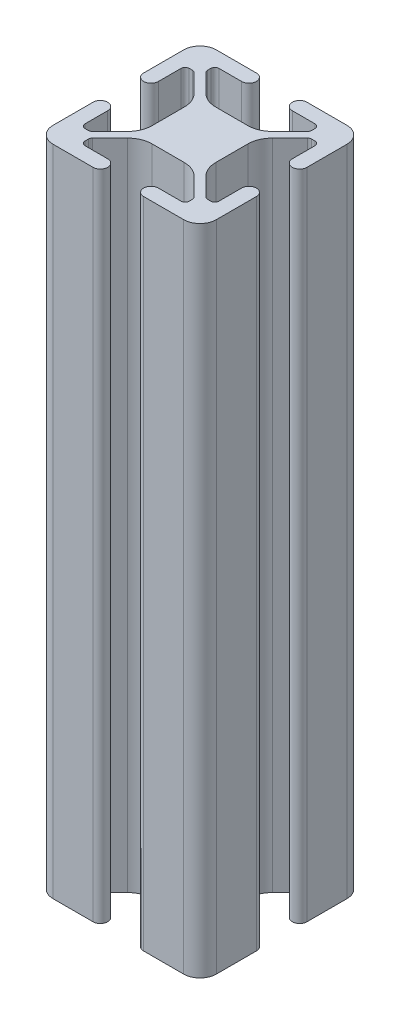
SolidWorks part; units mm, degrees
ref_plane "前视基准面" through (0, 0, 0) normal (0, 0, 1) x (1, 0, 0)
ref_plane "上视基准面" through (0, 0, 0) normal (0, 1, 0) x (1, 0, 0)
ref_plane "右视基准面" through (0, 0, 0) normal (1, 0, 0) x (0, 0, -1)
sketch "草图1" plane through (0, 0, 0) normal (0, 1, 0) x (1, 0, 0)
  line L0 (-1.0428, -10.0859) -> (3.8572, -10.0859)
  line L1 (1.0762, -11.8859) -> (3.8572, -11.8859)
  line L2 (2.8854, -15.3072) -> (0.7226, -13.1443)
  line L3 (2.1786, -16.0141) -> (0.0157, -13.8512)
  line L4 (-3.0428, -12.0859) -> (-3.0428, -16.9859)
  line L5 (-1.2428, -14.2048) -> (-1.2428, -16.9859)
  line L6 (-0.7428, -13.7048) -> (-0.3378, -13.7048)
  line L7 (0.5762, -12.3859) -> (0.5762, -12.7908)
  line L8 (-1.0428, -30.0859) -> (3.8572, -30.0859)
  line L9 (1.0762, -28.2859) -> (3.8572, -28.2859)
  line L10 (2.8854, -24.8645) -> (0.7226, -27.0274)
  line L11 (2.1786, -24.1577) -> (0.0157, -26.3205)
  line L12 (-3.0428, -28.0859) -> (-3.0428, -23.1859)
  line L13 (-1.2428, -25.9669) -> (-1.2428, -23.1859)
  line L14 (-0.7428, -26.4669) -> (-0.3378, -26.4669)
  line L15 (0.5762, -27.7859) -> (0.5762, -27.3809)
  line L16 (14.9572, -10.0859) -> (10.0572, -10.0859)
  line L17 (12.8383, -11.8859) -> (10.0572, -11.8859)
  line L18 (11.029, -15.3072) -> (13.1919, -13.1443)
  line L19 (11.7359, -16.0141) -> (13.8988, -13.8512)
  line L20 (16.9572, -12.0859) -> (16.9572, -16.9859)
  line L21 (15.1572, -14.2048) -> (15.1572, -16.9859)
  line L22 (14.6572, -13.7048) -> (14.2523, -13.7048)
  line L23 (13.3383, -12.3859) -> (13.3383, -12.7908)
  line L24 (14.9572, -30.0859) -> (10.0572, -30.0859)
  line L25 (12.8383, -28.2859) -> (10.0572, -28.2859)
  line L26 (11.029, -24.8645) -> (13.1919, -27.0274)
  line L27 (11.7359, -24.1577) -> (13.8988, -26.3205)
  line L28 (16.9572, -28.0859) -> (16.9572, -23.1859)
  line L29 (15.1572, -25.9669) -> (15.1572, -23.1859)
  line L30 (14.6572, -26.4669) -> (14.2523, -26.4669)
  line L31 (13.3383, -27.7859) -> (13.3383, -27.3809)
  line L32 (5.0068, -16.1859) -> (8.9077, -16.1859)
  line L33 (10.8572, -18.1354) -> (10.8572, -22.0363)
  line L34 (3.0572, -18.1354) -> (3.0572, -22.0363)
  line L35 (5.0068, -23.9859) -> (8.9077, -23.9859)
  circle A0 centre (6.9572, -20.0859) radius 2.5
  arc A1 (2.8854, -15.3072) -> (5.0068, -16.1859) centre (5.0068, -13.1859) ccw
  arc A2 (3.0572, -18.1354) -> (2.1786, -16.0141) centre (0.0572, -18.1354) ccw
  arc A3 (3.8572, -11.8859) -> (3.8572, -10.0859) centre (3.8572, -10.9859) ccw
  arc A4 (0.5762, -12.7908) -> (0.7226, -13.1443) centre (1.0762, -12.7908) ccw
  arc A5 (0.0157, -13.8512) -> (-0.3378, -13.7048) centre (-0.3378, -14.2048) ccw
  arc A6 (-3.0428, -16.9859) -> (-1.2428, -16.9859) centre (-2.1428, -16.9859) ccw
  arc A7 (-1.0428, -10.0859) -> (-3.0428, -12.0859) centre (-1.0428, -12.0859) ccw
  arc A8 (-0.7428, -13.7048) -> (-1.2428, -14.2048) centre (-0.7428, -14.2048) ccw
  arc A9 (1.0762, -11.8859) -> (0.5762, -12.3859) centre (1.0762, -12.3859) ccw
  arc A10 (5.0068, -23.9859) -> (2.8854, -24.8645) centre (5.0068, -26.9859) ccw
  arc A11 (2.1786, -24.1577) -> (3.0572, -22.0363) centre (0.0572, -22.0363) ccw
  arc A12 (3.8572, -30.0859) -> (3.8572, -28.2859) centre (3.8572, -29.1859) ccw
  arc A13 (0.7226, -27.0274) -> (0.5762, -27.3809) centre (1.0762, -27.3809) ccw
  arc A14 (-0.3378, -26.4669) -> (0.0157, -26.3205) centre (-0.3378, -25.9669) ccw
  arc A15 (-1.2428, -23.1859) -> (-3.0428, -23.1859) centre (-2.1428, -23.1859) ccw
  arc A16 (-3.0428, -28.0859) -> (-1.0428, -30.0859) centre (-1.0428, -28.0859) ccw
  arc A17 (-1.2428, -25.9669) -> (-0.7428, -26.4669) centre (-0.7428, -25.9669) ccw
  arc A18 (0.5762, -27.7859) -> (1.0762, -28.2859) centre (1.0762, -27.7859) ccw
  arc A19 (8.9077, -16.1859) -> (11.029, -15.3072) centre (8.9077, -13.1859) ccw
  arc A20 (11.7359, -16.0141) -> (10.8572, -18.1354) centre (13.8572, -18.1354) ccw
  arc A21 (10.0572, -10.0859) -> (10.0572, -11.8859) centre (10.0572, -10.9859) ccw
  arc A22 (13.1919, -13.1443) -> (13.3383, -12.7908) centre (12.8383, -12.7908) ccw
  arc A23 (14.2523, -13.7048) -> (13.8988, -13.8512) centre (14.2523, -14.2048) ccw
  arc A24 (15.1572, -16.9859) -> (16.9572, -16.9859) centre (16.0572, -16.9859) ccw
  arc A25 (16.9572, -12.0859) -> (14.9572, -10.0859) centre (14.9572, -12.0859) ccw
  arc A26 (15.1572, -14.2048) -> (14.6572, -13.7048) centre (14.6572, -14.2048) ccw
  arc A27 (13.3383, -12.3859) -> (12.8383, -11.8859) centre (12.8383, -12.3859) ccw
  arc A28 (11.029, -24.8645) -> (8.9077, -23.9859) centre (8.9077, -26.9859) ccw
  arc A29 (10.8572, -22.0363) -> (11.7359, -24.1577) centre (13.8572, -22.0363) ccw
  arc A30 (10.0572, -28.2859) -> (10.0572, -30.0859) centre (10.0572, -29.1859) ccw
  arc A31 (13.3383, -27.3809) -> (13.1919, -27.0274) centre (12.8383, -27.3809) ccw
  arc A32 (13.8988, -26.3205) -> (14.2523, -26.4669) centre (14.2523, -25.9669) ccw
  arc A33 (16.9572, -23.1859) -> (15.1572, -23.1859) centre (16.0572, -23.1859) ccw
  arc A34 (14.9572, -30.0859) -> (16.9572, -28.0859) centre (14.9572, -28.0859) ccw
  arc A35 (14.6572, -26.4669) -> (15.1572, -25.9669) centre (14.6572, -25.9669) ccw
  arc A36 (12.8383, -28.2859) -> (13.3383, -27.7859) centre (12.8383, -27.7859) ccw
extrude "凸台-拉伸1" add sketch "草图1" along normal blind 80 contours L32 A19 L18 A22 L23 A27 L17 A21 L16 A25 L20 A24 L21 A26 L22 A23 L19 A20 L33 A29 L27 A32 L30 A35 L29 A33 L28 A34 L24 A30 L25 A36 L31 A31 L26 A28 L35 A10 L10 A13 L15 A18 L9 A12 L8 A16 L12 A15 L13 A17 L14 A14 L11 A11 L34 A2 L3 A5 L6 A8 L5 A6 L4 A7 L0 A3 L1 A9 L7 A4 L2 A1
ref_plane "基准面1" through (0, 40, 0) normal (0, 1, 0) x (1, 0, 0)
ref_plane "基准面2" through (6.9572, 0, 0) normal (-1, 0, 0) x (0, 0, 1)
